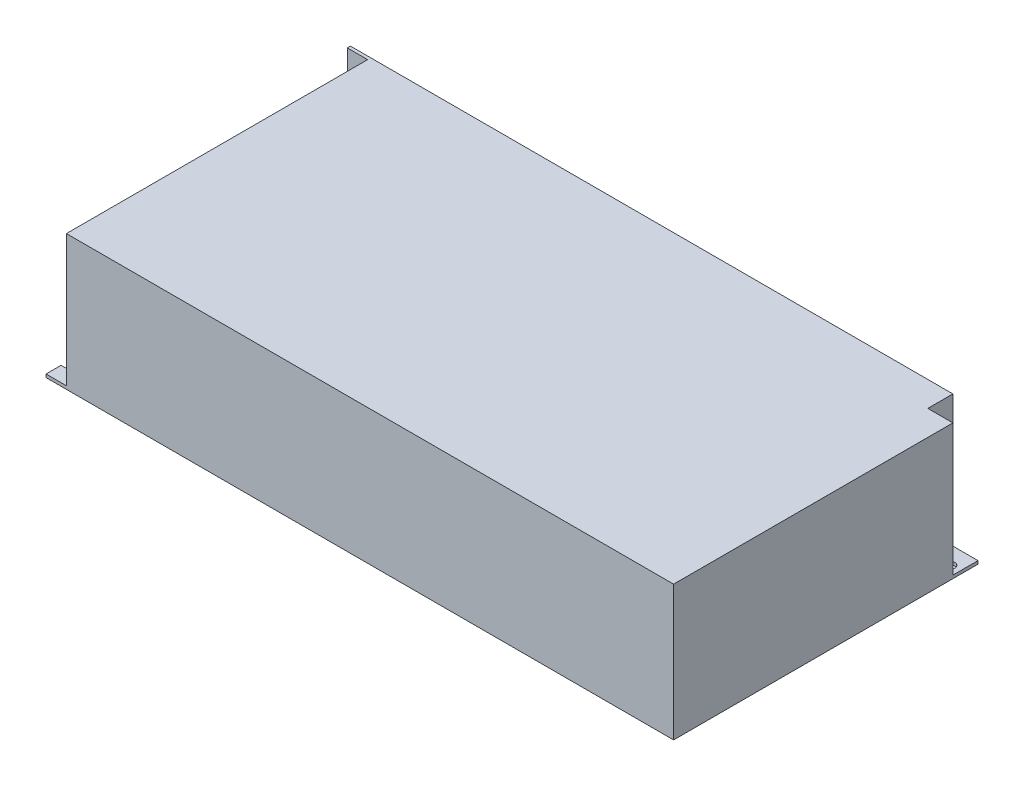
SolidWorks part; units mm, degrees
ref_plane "Front Plane" through (0, 0, 0) normal (0, 0, 1) x (1, 0, 0)
ref_plane "Top Plane" through (0, 0, 0) normal (0, 1, 0) x (1, 0, 0)
ref_plane "Right Plane" through (0, 0, 0) normal (1, 0, 0) x (0, 0, -1)
sketch "Sketch1" plane through (0, 0, 0) normal (0, 1, 0) x (1, 0, 0)
  line L1 (-100, 48.5) -> (100, 48.5)
  line L2 (-100, 48.5) -> (-100, -48.5)
  line L3 (-100, -48.5) -> (100, -48.5)
  line L4 (100, 48.5) -> (100, -48.5)
  line L5 (-100, 48.5) -> (100, -48.5) construction
  line L6 (-100, -48.5) -> (100, 48.5) construction
  point P0 (0, 0)
  dimension "D1" = 200
  dimension "D2" = 97
extrude "Boss-Extrude1" add sketch "Sketch1" along normal blind 43
sketch "Sketch2" plane through (0, 0, 48.5) normal (0, 0, 1) x (1, 0, 0)
  line L0 (-93.5, 43) -> (-93.5, 17.5)
  line L1 (-100, 43) -> (100, 43) construction
  line L2 (-100, 43) -> (-100, 0) construction
  line L4 (-93.5, 43) -> (-100, 43)
  line L5 (-100, 43) -> (-100, 2.0701)
  arc A0 (-93.5, 17.5) -> (-96.8492, 8.6362) centre (-106.9038, 17.5) cw
  arc A1 (-96.8492, 8.6362) -> (-100, 2.0701) centre (-86.7946, -0.2276) ccw
  dimension "D1" = 25.5
  dimension "D2" = 6.5
extrude "Cut-Extrude1" cut sketch "Sketch2" against normal offset from surface (96 mm away) 1 up to face at (0, 21.5, -48.5)
sketch "Sketch3" plane through (0, 43, 0) normal (0, 1, 0) x (1, 0, 0)
  line L0 (-93.5, 47.5) -> (-93.5, -48.5) construction
  line L1 (-100, -48.5) -> (-93.5, -48.5)
  line L2 (-100, -48.5) -> (-100, -35.5)
  line L3 (-100, -35.5) -> (-93.5, -35.5)
  line L4 (-93.5, -48.5) -> (-93.5, -35.5)
  line L6 (100, 48.5) -> (92, 48.5)
  line L7 (100, 48.5) -> (100, 40.5)
  line L8 (100, 40.5) -> (92, 40.5)
  line L9 (92, 48.5) -> (92, 40.5)
  dimension "D1" = 8
  dimension "8" = 8
  dimension "D2" = 13
extrude "Cut-Extrude2" cut sketch "Sketch3" against normal offset from surface (42 mm away) 1 up to face at (0, 0, 0)
sketch "Sketch4" plane through (0, 1, 0) normal (0, 1, 0) x (1, 0, 0)
  line L0 (-97.0019, -41.8) -> (-106.1653, -41.8) construction
  line L1 (-97.0019, -43.7) -> (-106.1653, -43.7)
  line L2 (-97.0019, -39.9) -> (-106.1653, -39.9)
  line L3 (-93.5, -48.5) -> (-100, -48.5) construction
  line L4 (100, 48.5) -> (100, 40.5) construction
  line L5 (92, 48.5) -> (100, 48.5) construction
  arc A0 (-97.0019, -43.7) -> (-97.0019, -39.9) centre (-97.0019, -41.8) ccw
  arc A1 (-106.1653, -39.9) -> (-106.1653, -43.7) centre (-106.1653, -41.8) ccw
  circle A2 centre (96.8, 42.7) radius 1.6
  point P2 (-101.5836, -41.8)
  dimension "D1" = 1.9
  dimension "D3" = 3.2
  dimension "D2" = 6.7
  dimension "D4" = 3.2
  dimension "D5" = 5.8
extrude "Cut-Extrude3" cut sketch "Sketch4" against normal through all
